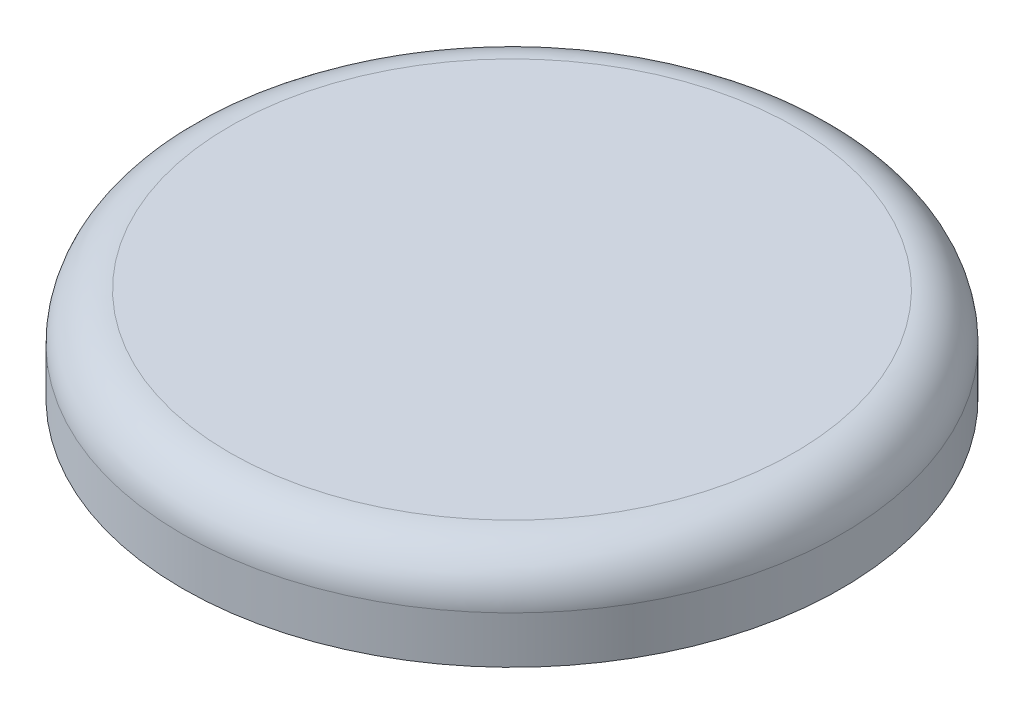
SolidWorks part; units mm, degrees
ref_plane "Front Plane" through (0, 0, 0) normal (0, 0, 1) x (1, 0, 0)
ref_plane "Top Plane" through (0, 0, 0) normal (0, 1, 0) x (1, 0, 0)
ref_plane "Right Plane" through (0, 0, 0) normal (1, 0, 0) x (0, 0, -1)
sketch "Sketch1" plane through (0, 0, 0) normal (0, 1, 0) x (1, 0, 0)
  circle A0 centre (0, 0) radius 35
  dimension "D1" = 70
extrude "Boss-Extrude1" add sketch "Sketch1" along normal blind 10
fillet "Fillet1" radius 5 1 edges at (0, 10, 35)
sketch "Sketch2" plane through (0, 0, 0) normal (0, -1, 0) x (1, 0, 0)
  circle A0 centre (0, 0) radius 10
  dimension "D1" = 20
extrude "Cut-Extrude1" cut sketch "Sketch2" against normal blind 5
